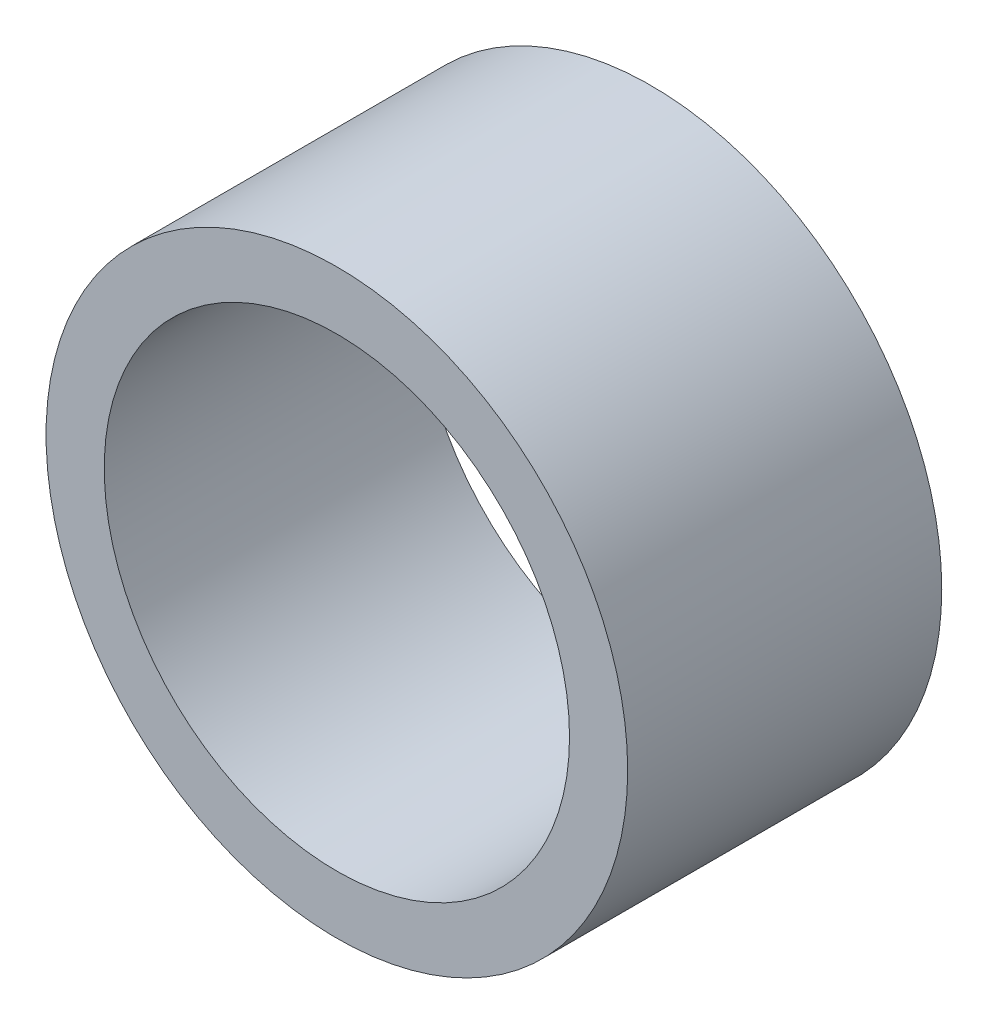
SolidWorks part; units mm, degrees
ref_plane "Front Plane" through (0, 0, 0) normal (0, 0, 1) x (1, 0, 0)
ref_plane "Top Plane" through (0, 0, 0) normal (0, 1, 0) x (1, 0, 0)
ref_plane "Right Plane" through (0, 0, 0) normal (1, 0, 0) x (0, 0, -1)
sketch "Sketch1" plane through (0, 0, 0) normal (1, 0, 0) x (0, 0, -1)
  line L0 (-20.7004, 0) -> (18.1553, 0) construction
  line L1 (2.75, 0) -> (-2.75, 0) construction
  line L2 (0, 2.75) -> (0, -2.75) construction
  line L3 (0, 2.5) -> (2.7, 2.5)
  line L4 (2.7, 2.5) -> (2.7, 1.5)
  line L5 (2.7, 1.5) -> (4, 1.5)
  line L6 (4, 1.5) -> (4, 0.5)
  line L7 (4, 0.5) -> (2, 0.5)
  line L8 (2, 0.5) -> (2, 2)
  line L9 (2, 2) -> (0, 2)
  line L10 (0, 2) -> (0, 2.5)
  dimension "D1" = 5
  dimension "D2" = 4
  dimension "D3" = 2
  dimension "D4" = 0.7
  dimension "D5" = 2
  dimension "D6" = 1
  dimension "D7" = 1
revolve "Revolve1" add sketch "Sketch1" angle 360 about L0
sketch "Skizze1" plane through (0, 0, -2) normal (0, 0, 1) x (1, 0, 0)
  circle A1 centre (0, 0) radius 2 construction
  circle A2 centre (0, 0) radius 2
extrude "Schnitt-Linear austragen1" cut sketch "Skizze1" against normal through all
